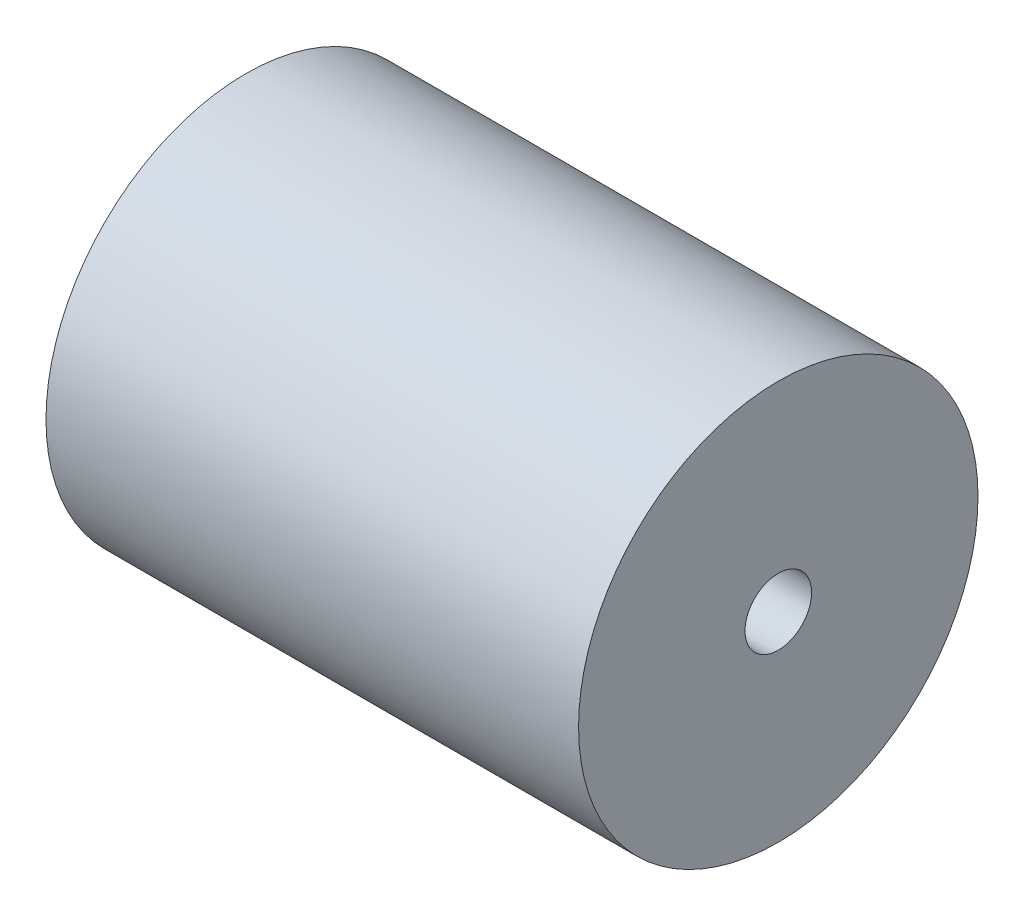
SolidWorks part; units mm, degrees
ref_plane "Front Plane" through (0, 0, 0) normal (0, 0, 1) x (1, 0, 0)
ref_plane "Top Plane" through (0, 0, 0) normal (0, 1, 0) x (1, 0, 0)
ref_plane "Right Plane" through (0, 0, 0) normal (1, 0, 0) x (0, 0, -1)
sketch "Sketch1" plane through (0, 0, 0) normal (1, 0, 0) x (0, 0, -1)
  circle A0 centre (0, 0) radius 1.5
  dimension "D1" = 3
extrude "Boss-Extrude1" add sketch "Sketch1" along normal blind 4
sketch "Sketch2" plane through (4, 0, 0) normal (1, 0, 0) x (0, 0, -1)
  circle A0 centre (0, 0) radius 0.25
  dimension "D1" = 0.5
extrude "Cut-Extrude1" cut sketch "Sketch2" against normal blind 4
